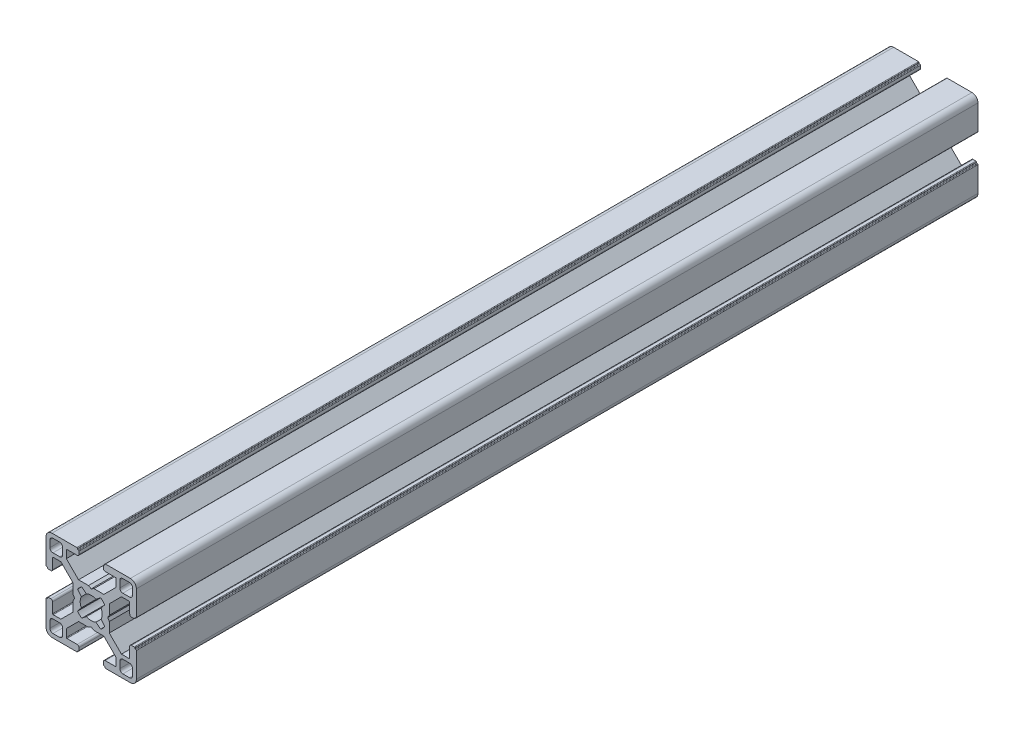
SolidWorks part; units mm, degrees
material "6061 Alloy"
ref_plane "Front" through (0, 0, 0) normal (0, 0, 1) x (1, 0, 0)
ref_plane "Top" through (0, 0, 0) normal (0, 1, 0) x (1, 0, 0)
ref_plane "Right" through (0, 0, 0) normal (1, 0, 0) x (0, 0, -1)
sketch "Sketch1" plane through (0, 0, 0) normal (0, 0, 1) x (1, 0, 0)
  line L0 (13.7, 12.7) -> (13.7, 10.5)
  line L1 (10.5, 9.5) -> (12.7, 9.5)
  line L2 (9.5, 12.7) -> (9.5, 10.5)
  line L3 (10.5, 13.7) -> (12.7, 13.7)
  line L4 (3.1359, 4.5184) -> (1.6001, 3.2806)
  line L5 (3.2806, 1.6001) -> (4.5053, 3.1547)
  line L6 (6.0045, 0.9) -> (5.4849, 0)
  line L7 (6.0045, 4.2045) -> (6.0045, 0.9)
  line L8 (0, -5.4849) -> (0.9, -6)
  line L9 (0.9, -6) -> (4.2045, -6)
  line L10 (4.2045, -6) -> (8.25, -10.05)
  line L11 (8.25, -10.05) -> (8.25, -12.6)
  line L12 (4.65, -12.8) -> (8.05, -12.8)
  line L13 (4.05, -14.3) -> (4.05, -13.4)
  line L14 (4.25, -14.5) -> (4.35, -14.5)
  line L15 (4.55, -14.8) -> (4.55, -14.7)
  line L16 (4.75, -15) -> (13, -15)
  line L17 (15, -13) -> (15, -4.75)
  line L18 (14.7, -4.55) -> (14.8, -4.55)
  line L19 (14.5, -4.35) -> (14.5, -4.25)
  line L20 (13.4, -4.05) -> (14.3, -4.05)
  line L21 (12.8, -8.05) -> (12.8, -4.65)
  line L22 (12.6, -8.25) -> (10.05, -8.25)
  line L23 (10.05, -8.25) -> (6.0045, -4.2045)
  line L24 (6.0045, -4.2045) -> (6.0045, -0.9)
  line L25 (6.0045, -0.9) -> (5.4849, 0)
  line L26 (10.05, 8.25) -> (6.0045, 4.2045)
  line L27 (12.6, 8.25) -> (10.05, 8.25)
  line L28 (12.8, 8.05) -> (12.8, 4.65)
  line L29 (13.4, 4.05) -> (14.3, 4.05)
  line L30 (14.5, 4.35) -> (14.5, 4.25)
  line L31 (14.7, 4.55) -> (14.8, 4.55)
  line L32 (15, 13) -> (15, 4.75)
  line L33 (4.75, 15) -> (13, 15)
  line L34 (4.55, 14.8) -> (4.55, 14.7)
  line L35 (4.25, 14.5) -> (4.35, 14.5)
  line L36 (4.05, 14.3) -> (4.05, 13.4)
  line L37 (4.65, 12.8) -> (8.05, 12.8)
  line L38 (8.25, 10.05) -> (8.25, 12.6)
  line L39 (4.2045, 6) -> (8.25, 10.05)
  line L40 (0.9, 6) -> (4.2045, 6)
  line L41 (0, 5.4849) -> (0.9, 6)
  line L42 (-13.7, -12.7) -> (-13.7, -10.5)
  line L43 (-10.5, -9.5) -> (-12.7, -9.5)
  line L44 (-9.5, -12.7) -> (-9.5, -10.5)
  line L45 (-10.5, -13.7) -> (-12.7, -13.7)
  line L46 (-3.1359, -4.5184) -> (-1.6001, -3.2806)
  line L47 (-3.2806, -1.6001) -> (-4.5053, -3.1547)
  line L48 (0, 5.4849) -> (-0.9, 6)
  line L49 (-0.9, 6) -> (-4.2045, 6)
  line L50 (-4.2045, 6) -> (-8.25, 10.05)
  line L51 (-8.25, 10.05) -> (-8.25, 12.6)
  line L52 (-4.65, 12.8) -> (-8.05, 12.8)
  line L53 (-4.05, 14.3) -> (-4.05, 13.4)
  line L54 (-4.25, 14.5) -> (-4.35, 14.5)
  line L55 (-4.55, 14.8) -> (-4.55, 14.7)
  line L56 (-4.75, 15) -> (-13, 15)
  line L57 (-15, 13) -> (-15, 4.75)
  line L58 (-14.7, 4.55) -> (-14.8, 4.55)
  line L59 (-14.5, 4.35) -> (-14.5, 4.25)
  line L60 (-13.4, 4.05) -> (-14.3, 4.05)
  line L61 (-12.8, 8.05) -> (-12.8, 4.65)
  line L62 (-12.6, 8.25) -> (-10.05, 8.25)
  line L63 (-10.05, 8.25) -> (-6.0045, 4.2045)
  line L64 (-6.0045, -0.9) -> (-5.4849, 0)
  line L65 (-6.0045, -4.2045) -> (-6.0045, -0.9)
  line L66 (-10.05, -8.25) -> (-6.0045, -4.2045)
  line L67 (-12.6, -8.25) -> (-10.05, -8.25)
  line L68 (-12.8, -8.05) -> (-12.8, -4.65)
  line L69 (-13.4, -4.05) -> (-14.3, -4.05)
  line L70 (-14.5, -4.35) -> (-14.5, -4.25)
  line L71 (-14.7, -4.55) -> (-14.8, -4.55)
  line L72 (-15, -13) -> (-15, -4.75)
  line L73 (-4.75, -15) -> (-13, -15)
  line L74 (-4.55, -14.8) -> (-4.55, -14.7)
  line L75 (-4.25, -14.5) -> (-4.35, -14.5)
  line L76 (-4.05, -14.3) -> (-4.05, -13.4)
  line L77 (3.2806, -1.6001) -> (4.5053, -3.1547)
  line L78 (3.1359, -4.5184) -> (1.6001, -3.2806)
  line L79 (-4.65, -12.8) -> (-8.05, -12.8)
  line L80 (-8.25, -10.05) -> (-8.25, -12.6)
  line L81 (-4.2045, -6) -> (-8.25, -10.05)
  line L82 (-0.9, -6) -> (-4.2045, -6)
  line L83 (0, -5.4849) -> (-0.9, -6)
  line L84 (10.5, -13.7) -> (12.7, -13.7)
  line L85 (9.5, -12.7) -> (9.5, -10.5)
  line L86 (10.5, -9.5) -> (12.7, -9.5)
  line L87 (13.7, -12.7) -> (13.7, -10.5)
  line L88 (-6.0045, 4.2045) -> (-6.0045, 0.9)
  line L89 (-6.0045, 0.9) -> (-5.4849, 0)
  line L90 (-3.2806, 1.6001) -> (-4.5053, 3.1547)
  line L91 (-3.1359, 4.5184) -> (-1.6001, 3.2806)
  line L92 (-10.5, 13.7) -> (-12.7, 13.7)
  line L93 (-9.5, 12.7) -> (-9.5, 10.5)
  line L94 (-10.5, 9.5) -> (-12.7, 9.5)
  line L95 (-13.7, 12.7) -> (-13.7, 10.5)
  line L96 (-23.4857, 0) -> (20.9308, 0) construction
  line L97 (0, 17.9563) -> (0, -17.361) construction
  arc A0 (13.7, 12.7) -> (12.7, 13.7) centre (12.7, 12.7) ccw
  arc A1 (12.7, 9.5) -> (13.7, 10.5) centre (12.7, 10.5) ccw
  arc A2 (9.5, 10.5) -> (10.5, 9.5) centre (10.5, 10.5) ccw
  arc A3 (10.5, 13.7) -> (9.5, 12.7) centre (10.5, 12.7) ccw
  arc A4 (1.6001, 3.2806) -> (-1.6001, 3.2806) centre (0, 0) ccw
  arc A5 (8.25, -12.6) -> (8.05, -12.8) centre (8.05, -12.6) cw
  arc A6 (4.65, -12.8) -> (4.05, -13.4) centre (4.65, -13.4) ccw
  arc A7 (4.05, -14.3) -> (4.25, -14.5) centre (4.25, -14.3) ccw
  arc A8 (4.35, -14.5) -> (4.55, -14.7) centre (4.35, -14.7) cw
  arc A9 (4.55, -14.8) -> (4.75, -15) centre (4.75, -14.8) ccw
  arc A10 (13, -15) -> (15, -13) centre (13, -13) ccw
  arc A11 (15, -4.75) -> (14.8, -4.55) centre (14.8, -4.75) ccw
  arc A12 (14.7, -4.55) -> (14.5, -4.35) centre (14.7, -4.35) cw
  arc A13 (14.5, -4.25) -> (14.3, -4.05) centre (14.3, -4.25) ccw
  arc A14 (13.4, -4.05) -> (12.8, -4.65) centre (13.4, -4.65) ccw
  arc A15 (12.8, -8.05) -> (12.6, -8.25) centre (12.6, -8.05) cw
  arc A16 (4.5053, 3.1547) -> (3.1359, 4.5184) centre (0, 0) ccw
  arc A17 (12.8, 8.05) -> (12.6, 8.25) centre (12.6, 8.05) ccw
  arc A18 (13.4, 4.05) -> (12.8, 4.65) centre (13.4, 4.65) cw
  arc A19 (14.5, 4.25) -> (14.3, 4.05) centre (14.3, 4.25) cw
  arc A20 (14.7, 4.55) -> (14.5, 4.35) centre (14.7, 4.35) ccw
  arc A21 (15, 4.75) -> (14.8, 4.55) centre (14.8, 4.75) cw
  arc A22 (13, 15) -> (15, 13) centre (13, 13) cw
  arc A23 (4.55, 14.8) -> (4.75, 15) centre (4.75, 14.8) cw
  arc A24 (4.35, 14.5) -> (4.55, 14.7) centre (4.35, 14.7) ccw
  arc A25 (4.05, 14.3) -> (4.25, 14.5) centre (4.25, 14.3) cw
  arc A26 (4.65, 12.8) -> (4.05, 13.4) centre (4.65, 13.4) cw
  arc A27 (8.25, 12.6) -> (8.05, 12.8) centre (8.05, 12.6) ccw
  arc A28 (-13.7, -12.7) -> (-12.7, -13.7) centre (-12.7, -12.7) ccw
  arc A29 (-12.7, -9.5) -> (-13.7, -10.5) centre (-12.7, -10.5) ccw
  arc A30 (-9.5, -10.5) -> (-10.5, -9.5) centre (-10.5, -10.5) ccw
  arc A31 (-10.5, -13.7) -> (-9.5, -12.7) centre (-10.5, -12.7) ccw
  arc A32 (-4.5053, -3.1547) -> (-3.1359, -4.5184) centre (0, 0) ccw
  arc A33 (-3.2806, 1.6001) -> (-3.2806, -1.6001) centre (0, 0) ccw
  arc A34 (-8.25, 12.6) -> (-8.05, 12.8) centre (-8.05, 12.6) cw
  arc A35 (-4.65, 12.8) -> (-4.05, 13.4) centre (-4.65, 13.4) ccw
  arc A36 (-4.05, 14.3) -> (-4.25, 14.5) centre (-4.25, 14.3) ccw
  arc A37 (-4.35, 14.5) -> (-4.55, 14.7) centre (-4.35, 14.7) cw
  arc A38 (-4.55, 14.8) -> (-4.75, 15) centre (-4.75, 14.8) ccw
  arc A39 (-13, 15) -> (-15, 13) centre (-13, 13) ccw
  arc A40 (-15, 4.75) -> (-14.8, 4.55) centre (-14.8, 4.75) ccw
  arc A41 (-14.7, 4.55) -> (-14.5, 4.35) centre (-14.7, 4.35) cw
  arc A42 (-14.5, 4.25) -> (-14.3, 4.05) centre (-14.3, 4.25) ccw
  arc A43 (-13.4, 4.05) -> (-12.8, 4.65) centre (-13.4, 4.65) ccw
  arc A44 (-12.8, 8.05) -> (-12.6, 8.25) centre (-12.6, 8.05) cw
  arc A45 (-4.5053, 3.1547) -> (-3.1359, 4.5184) centre (0, 0) cw
  arc A46 (-12.8, -8.05) -> (-12.6, -8.25) centre (-12.6, -8.05) ccw
  arc A47 (-13.4, -4.05) -> (-12.8, -4.65) centre (-13.4, -4.65) cw
  arc A48 (-14.5, -4.25) -> (-14.3, -4.05) centre (-14.3, -4.25) cw
  arc A49 (3.2806, 1.6001) -> (3.2806, -1.6001) centre (0, 0) cw
  arc A50 (4.5053, -3.1547) -> (3.1359, -4.5184) centre (0, 0) cw
  arc A51 (1.6001, -3.2806) -> (-1.6001, -3.2806) centre (0, 0) cw
  arc A52 (-14.7, -4.55) -> (-14.5, -4.35) centre (-14.7, -4.35) ccw
  arc A53 (-15, -4.75) -> (-14.8, -4.55) centre (-14.8, -4.75) cw
  arc A54 (-13, -15) -> (-15, -13) centre (-13, -13) cw
  arc A55 (-4.55, -14.8) -> (-4.75, -15) centre (-4.75, -14.8) cw
  arc A56 (10.5, -13.7) -> (9.5, -12.7) centre (10.5, -12.7) cw
  arc A57 (9.5, -10.5) -> (10.5, -9.5) centre (10.5, -10.5) cw
  arc A58 (12.7, -9.5) -> (13.7, -10.5) centre (12.7, -10.5) cw
  arc A59 (13.7, -12.7) -> (12.7, -13.7) centre (12.7, -12.7) cw
  arc A60 (-4.35, -14.5) -> (-4.55, -14.7) centre (-4.35, -14.7) ccw
  arc A61 (-4.05, -14.3) -> (-4.25, -14.5) centre (-4.25, -14.3) cw
  arc A62 (-4.65, -12.8) -> (-4.05, -13.4) centre (-4.65, -13.4) cw
  arc A63 (-8.25, -12.6) -> (-8.05, -12.8) centre (-8.05, -12.6) ccw
  arc A64 (-10.5, 13.7) -> (-9.5, 12.7) centre (-10.5, 12.7) cw
  arc A65 (-9.5, 10.5) -> (-10.5, 9.5) centre (-10.5, 10.5) cw
  arc A66 (-12.7, 9.5) -> (-13.7, 10.5) centre (-12.7, 10.5) cw
  arc A67 (-13.7, 12.7) -> (-12.7, 13.7) centre (-12.7, 12.7) cw
  point P81 (15, 15)
  point P82 (0, 15)
  point P203 (0, -15)
  point P204 (15, -15)
  point P206 (0, 0)
  point P207 (15, 0)
  point P219 (-15, 0)
  point P220 (-15, -15)
  point P221 (-15, 15)
  dimension "D6" = 7.3
  dimension "D7" = 11
  dimension "D1" = 30
  dimension "D2" = 15
  dimension "D3" = 30
  dimension "D4" = 8.1
  dimension "D5" = 9
  dimension "D8" = 8.1
extrude "Boss-Extrude1" add sketch "Sketch1" along normal blind 279.4
